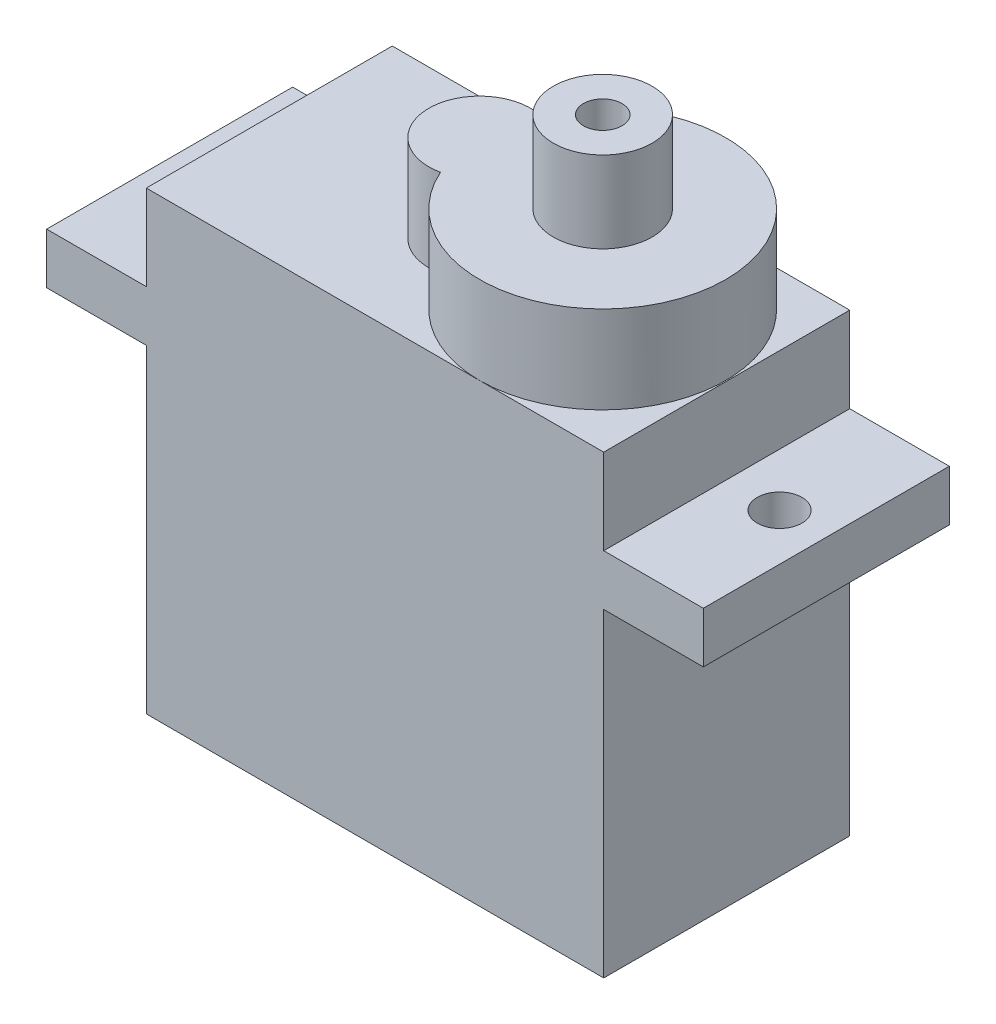
SolidWorks part; units mm, degrees
ref_plane "Front Plane" through (0, 0, 0) normal (0, 0, 1) x (1, 0, 0)
ref_plane "Top Plane" through (0, 0, 0) normal (0, 1, 0) x (1, 0, 0)
ref_plane "Right Plane" through (0, 0, 0) normal (1, 0, 0) x (0, 0, -1)
sketch "Sketch2" plane through (0, 0, 0) normal (0, 1, 0) x (1, 0, 0)
  line L1 (11.25, -6.05) -> (-11.25, -6.05)
  line L2 (11.25, -6.05) -> (11.25, 6.05)
  line L3 (11.25, 6.05) -> (-11.25, 6.05)
  line L4 (-11.25, -6.05) -> (-11.25, 6.05)
  line L5 (11.25, -6.05) -> (-11.25, 6.05) construction
  line L6 (11.25, 6.05) -> (-11.25, -6.05) construction
  point P0 (0, 0)
  dimension "D1" = 22.5
  dimension "D2" = 12.1
extrude "Boss-Extrude1" add sketch "Sketch2" along normal blind 15.7
sketch "Sketch3" plane through (0, 15.7, 0) normal (0, 1, 0) x (1, 0, 0)
  line L0 (11.25, 6.05) -> (-11.25, 6.05) construction
  line L1 (16.15, -6.05) -> (-16.15, -6.05)
  line L2 (16.15, -6.05) -> (16.15, 6.05)
  line L3 (16.15, 6.05) -> (-16.15, 6.05)
  line L4 (-16.15, -6.05) -> (-16.15, 6.05)
  line L5 (16.15, -6.05) -> (-16.15, 6.05) construction
  line L6 (16.15, 6.05) -> (-16.15, -6.05) construction
  line L7 (-13.85, 0) -> (13.85, 0) construction
  circle A0 centre (-13.85, 0) radius 1.1
  circle A1 centre (13.85, 0) radius 1.1
  point P0 (0, 0)
  dimension "D2" = 2.2
  dimension "D1" = 32.3
  dimension "D3" = 27.7
extrude "Boss-Extrude2" add sketch "Sketch3" along normal blind 2.5
sketch "Sketch4" plane through (0, 18.2, 0) normal (0, 1, 0) x (1, 0, 0)
  line L4 (-11.25, 6.05) -> (-11.25, -6.05)
  line L5 (11.25, 6.05) -> (-11.25, 6.05)
  line L6 (11.25, -6.05) -> (11.25, 6.05)
  line L7 (-11.25, -6.05) -> (11.25, -6.05)
  line L8 (-11.25, 6.05) -> (-11.25, -6.05)
  line L9 (11.25, 6.05) -> (-11.25, 6.05)
  line L10 (11.25, -6.05) -> (11.25, 6.05)
  line L11 (-11.25, -6.05) -> (11.25, -6.05)
  dimension "D1" = 0
extrude "Boss-Extrude3" add sketch "Sketch4" along normal blind 4.2
sketch "Sketch5" plane through (0, 22.4, 0) normal (0, 1, 0) x (1, 0, 0)
  line L0 (0, 0) -> (5.15, 0) construction
  line L1 (11.25, 6.05) -> (-11.25, 6.05) construction
  arc A0 (-0.3835, -2.4461) -> (-0.3835, 2.4461) centre (5.15, 0) ccw
  arc A1 (-0.3835, 2.4461) -> (-0.3835, -2.4461) centre (-0.9, 0) ccw
  circle A2 centre (13.85, 0) radius 1.1 construction
  dimension "D1" = 8.7
  dimension "D2" = 2.5
extrude "Boss-Extrude4" add sketch "Sketch5" along normal blind 4.3
sketch "Sketch6" plane through (0, 26.7, 0) normal (0, 1, 0) x (1, 0, 0)
  circle A0 centre (5.15, 0) radius 2.43
  circle A1 centre (5.15, 0) radius 0.95
  dimension "D1" = 4.86
  dimension "D2" = 1.9
extrude "Boss-Extrude5" add sketch "Sketch6" along normal blind 4
